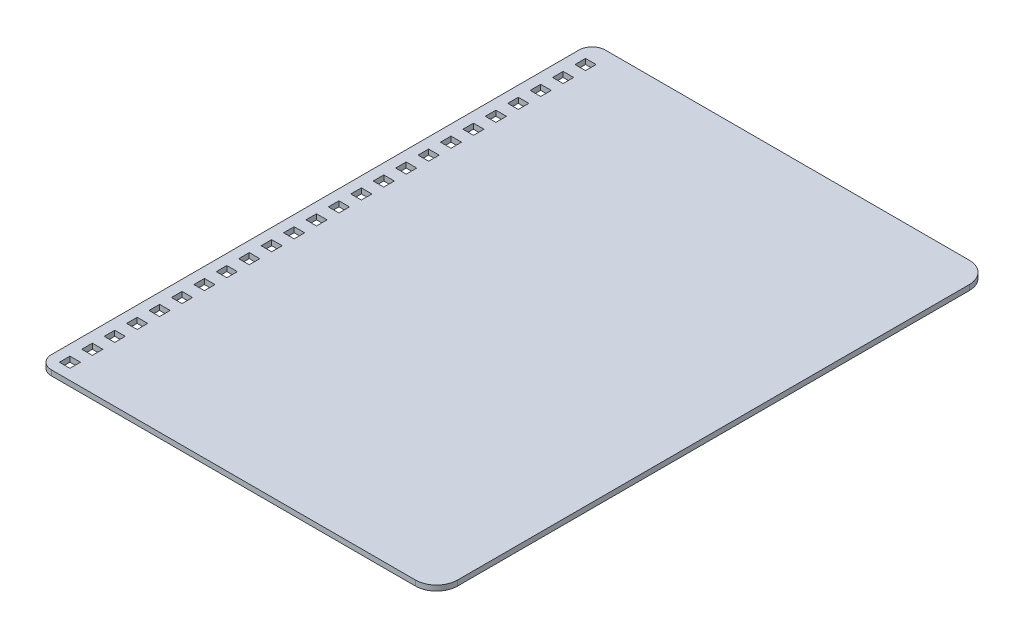
SolidWorks part; units mm, degrees
ref_plane "Front Plane" through (0, 0, 0) normal (0, 0, 1) x (1, 0, 0)
ref_plane "Top Plane" through (0, 0, 0) normal (0, 1, 0) x (1, 0, 0)
ref_plane "Right Plane" through (0, 0, 0) normal (1, 0, 0) x (0, 0, -1)
sketch "Sketch1" plane through (0, 0, 0) normal (0, 1, 0) x (1, 0, 0)
  line L1 (5, 0) -> (143, 0)
  line L2 (0, 5) -> (0, 205)
  line L3 (5, 210) -> (143, 210)
  line L4 (151, 8) -> (151, 202)
  arc A0 (143, 0) -> (151, 8) centre (143, 8) ccw
  arc A1 (143, 210) -> (151, 202) centre (143, 202) cw
  arc A2 (5, 0) -> (0, 5) centre (5, 5) cw
  arc A3 (0, 205) -> (5, 210) centre (5, 205) cw
  point P7 (151, 0)
  point P12 (0, 0)
  point P15 (0, 210)
  dimension "D3" = 8
  dimension "D4" = 5
  dimension "D1" = 210
  dimension "D2" = 151
extrude "Boss-Extrude1" add sketch "Sketch1" along normal blind 2
sketch "Sketch2" plane through (0, 2, 0) normal (0, 1, 0) x (1, 0, 0)
  line L0 (0, 205) -> (0, 5) construction
  line L1 (4, 203.5) -> (8, 203.5)
  line L2 (4, 203.5) -> (4, 199.5)
  line L3 (4, 199.5) -> (8, 199.5)
  line L4 (8, 203.5) -> (8, 199.5)
  line L5 (143, 210) -> (5, 210) construction
  dimension "D1" = 4
  dimension "D2" = 4
  dimension "D3" = 6.5
extrude "Cut-Extrude1" cut sketch "Sketch2" against normal blind 2
pattern_linear "LPattern1" count 24 spacing 8.5 along (0, 0, 1) of "Cut-Extrude1"
